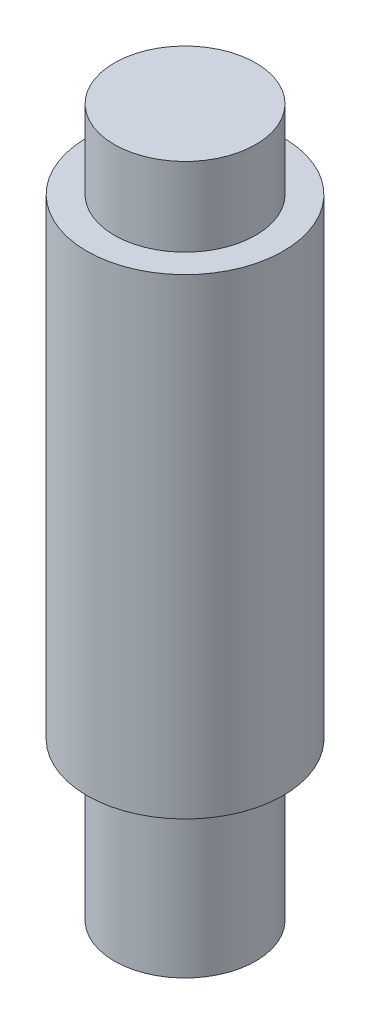
SolidWorks part; units mm, degrees
ref_plane "前视基准面" through (0, 0, 0) normal (0, 0, 1) x (1, 0, 0)
ref_plane "上视基准面" through (0, 0, 0) normal (0, 1, 0) x (1, 0, 0)
ref_plane "右视基准面" through (0, 0, 0) normal (1, 0, 0) x (0, 0, -1)
other "Configuration Table"
sketch "草图1" plane through (0, 0, 0) normal (0, 1, 0) x (1, 0, 0)
  circle A0 centre (0, 0) radius 0.9
  dimension "D1" = 1.8
extrude "凸台-拉伸1" add sketch "草图1" along normal blind 2
sketch "草图2" plane through (0, 2, 0) normal (0, 1, 0) x (1, 0, 0)
  circle A0 centre (0, 0) radius 1.25
  dimension "D1" = 2.5
extrude "凸台-拉伸2" add sketch "草图2" along normal blind 6
sketch "草图3" plane through (0, 8, 0) normal (0, 1, 0) x (1, 0, 0)
  circle A0 centre (0, 0) radius 0.9
  dimension "D1" = 1.8
extrude "凸台-拉伸3" add sketch "草图3" along normal blind 1
